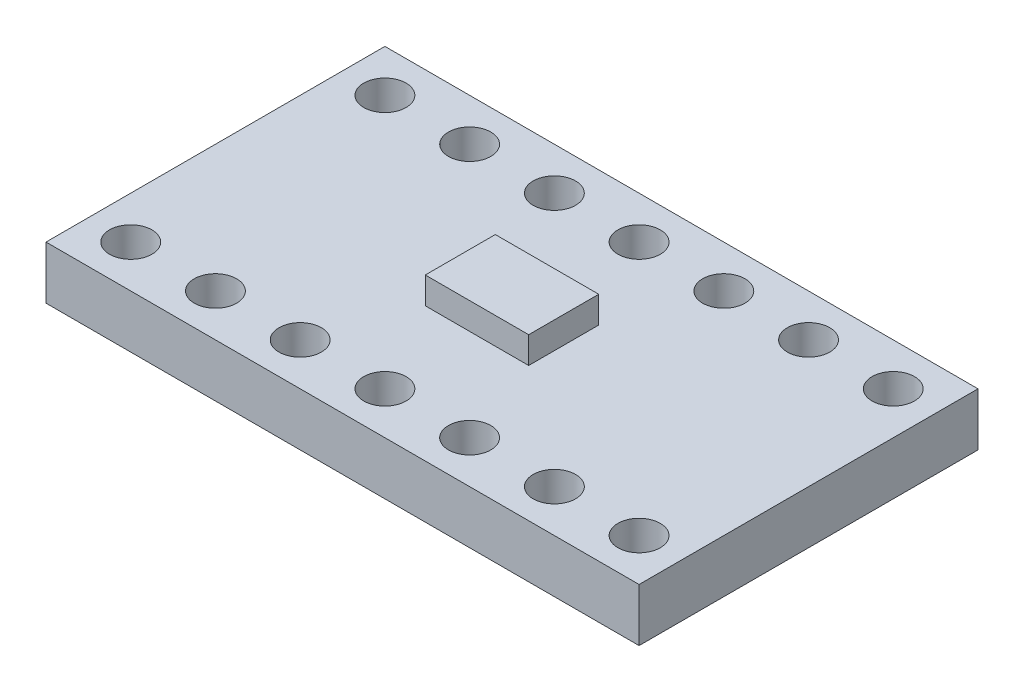
SolidWorks part; units mm, degrees
ref_plane "Front Plane" through (0, 0, 0) normal (0, 0, 1) x (1, 0, 0)
ref_plane "Top Plane" through (0, 0, 0) normal (0, 1, 0) x (1, 0, 0)
ref_plane "Right Plane" through (0, 0, 0) normal (1, 0, 0) x (0, 0, -1)
sketch "Sketch1" plane through (0, 0, 0) normal (0, 1, 0) x (1, 0, 0)
  line L1 (-8.89, 5.08) -> (8.89, 5.08)
  line L2 (-8.89, 5.08) -> (-8.89, -5.08)
  line L3 (-8.89, -5.08) -> (8.89, -5.08)
  line L4 (8.89, 5.08) -> (8.89, -5.08)
  line L5 (-8.89, 5.08) -> (8.89, -5.08) construction
  line L6 (-8.89, -5.08) -> (8.89, 5.08) construction
  point P0 (0, 0)
  dimension "D1" = 10.16
  dimension "D2" = 17.78
extrude "Boss-Extrude1" add sketch "Sketch1" against normal blind 1.5875
sketch "Sketch2" plane through (0, 0, 0) normal (0, 1, 0) x (1, 0, 0)
  line L1 (-1.55, 1.05) -> (1.55, 1.05)
  line L2 (-1.55, 1.05) -> (-1.55, -1.05)
  line L3 (-1.55, -1.05) -> (1.55, -1.05)
  line L4 (1.55, 1.05) -> (1.55, -1.05)
  line L5 (-1.55, 1.05) -> (1.55, -1.05) construction
  line L6 (-1.55, -1.05) -> (1.55, 1.05) construction
  point P0 (0, 0)
  dimension "D1" = 2.1
  dimension "D2" = 3.1
extrude "Boss-Extrude2" add sketch "Sketch2" along normal blind 0.8
sketch "Sketch3" plane through (0, 0, 0) normal (0, 1, 0) x (1, 0, 0)
  line L0 (-8.89, 5.08) -> (-8.89, -5.08) construction
  line L1 (8.89, 5.08) -> (-8.89, 5.08) construction
  line L2 (-11.2706, 0) -> (11.611, 0) construction
  circle A0 centre (-7.62, 3.81) radius 0.635
  circle A1 centre (-7.62, -3.81) radius 0.635
  circle A2 centre (-5.08, 3.81) radius 0.635
  circle A3 centre (-5.08, -3.81) radius 0.635
  circle A4 centre (-2.54, 3.81) radius 0.635
  circle A5 centre (-2.54, -3.81) radius 0.635
  circle A6 centre (0, 3.81) radius 0.635
  circle A7 centre (0, -3.81) radius 0.635
  circle A8 centre (2.54, 3.81) radius 0.635
  circle A9 centre (2.54, -3.81) radius 0.635
  circle A10 centre (5.08, 3.81) radius 0.635
  circle A11 centre (5.08, -3.81) radius 0.635
  circle A12 centre (7.62, 3.81) radius 0.635
  circle A13 centre (7.62, -3.81) radius 0.635
  dimension "D1" = 1.27
  dimension "D2" = 1.27
  dimension "D3" = 1.27
  dimension "D4" = 7
extrude "Cut-Extrude1" cut sketch "Sketch3" against normal up to next
